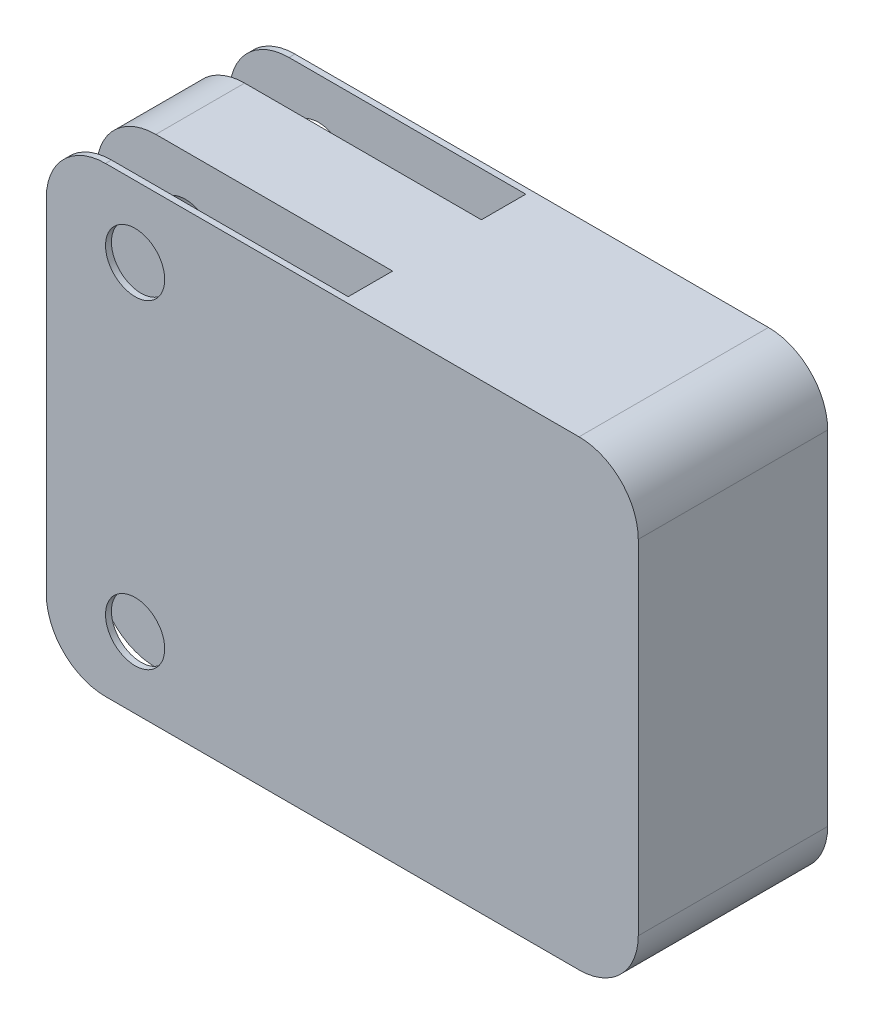
SolidWorks part; units mm, degrees
ref_plane "Front Plane" through (0, 0, 0) normal (1, 0, 0) x (0, 1, 0)
ref_plane "Top Plane" through (0, 0, 0) normal (0, 0, 1) x (0, 1, 0)
ref_plane "Right Plane" through (0, 0, 0) normal (0, 1, 0) x (-1, 0, 0)
sketch "Sketch1" plane through (0, 0, 0) normal (0, 0, 1) x (0, 1, 0)
  line L0 (0, 0) -> (0, 55) construction
  line L1 (39, -45) -> (-39, -45)
  line L2 (39, -45) -> (39, 55)
  line L3 (39, 55) -> (-39, 55)
  line L4 (-39, -45) -> (-39, 55)
  circle A0 centre (-27, 40) radius 5
  circle A1 centre (27, 40) radius 5
  point P0 (0, 0)
  dimension "D2" = 10
  dimension "D1" = 78
  dimension "D3" = 27
  dimension "D4" = 100
  dimension "D5" = 15
  dimension "D6" = 45
extrude "Boss-Extrude1" add sketch "Sketch1" along normal blind 15
fillet "Fillet1" radius 10 2 edges at (-55, -39, 7.5) (-55, 39, 7.5)
sketch "Sketch2" plane through (45, 0, 0) normal (1, 0, 0) x (0, 1, 0)
  line L0 (-39, 15) -> (-39, 22.5)
  line L1 (-39, 22.5) -> (39, 22.5)
  line L2 (39, 22.5) -> (39, 15)
  line L3 (39, 15) -> (-39, 15)
  line L4 (-39, 0) -> (-39, -7.5)
  line L5 (-39, -7.5) -> (39, -7.5)
  line L6 (39, -7.5) -> (39, 0)
  line L7 (29, 0) -> (39, 0) construction
  line L8 (-39, 0) -> (39, 0) construction
  line L9 (-39, 0) -> (39, 0)
  dimension "D1" = 7.5
  dimension "D2" = 7.5
  dimension "D3" = 78
extrude "Boss-Extrude2" add sketch "Sketch2" against normal blind 50
sketch "Sketch3" plane through (45, 0, 0) normal (1, 0, 0) x (0, 1, 0)
  line L0 (-39, 22.5) -> (-39, 23.5)
  line L1 (-39, 23.5) -> (39, 23.5)
  line L2 (39, 23.5) -> (39, 22.5)
  line L3 (39, 22.5) -> (-39, 22.5)
  line L4 (-39, -7.5) -> (-39, -8.5)
  line L5 (-39, -8.5) -> (39, -8.5)
  line L6 (39, -8.5) -> (39, -7.5)
  line L7 (39, -7.5) -> (-39, -7.5)
  dimension "D1" = 1
  dimension "D2" = 1
extrude "Boss-Extrude3" add sketch "Sketch3" against normal blind 100
fillet "Fillet2" radius 10 4 edges at (45, 39, 7.5) (-55, -39, -8) (45, -39, 7.5) (-55, 39, -8)
fillet "Fillet3" radius 10 2 edges at (-55, -39, 23) (-55, 39, 23)
sketch "Sketch4" plane through (0, 0, 23.5) normal (0, 0, 1) x (1, 0, 0)
  circle A0 centre (-40, 27) radius 5
  circle A1 centre (-40, -27) radius 5
  dimension "D1" = 10
  dimension "D2" = 10
extrude "Cut-Extrude1" cut sketch "Sketch4" against normal blind 100
